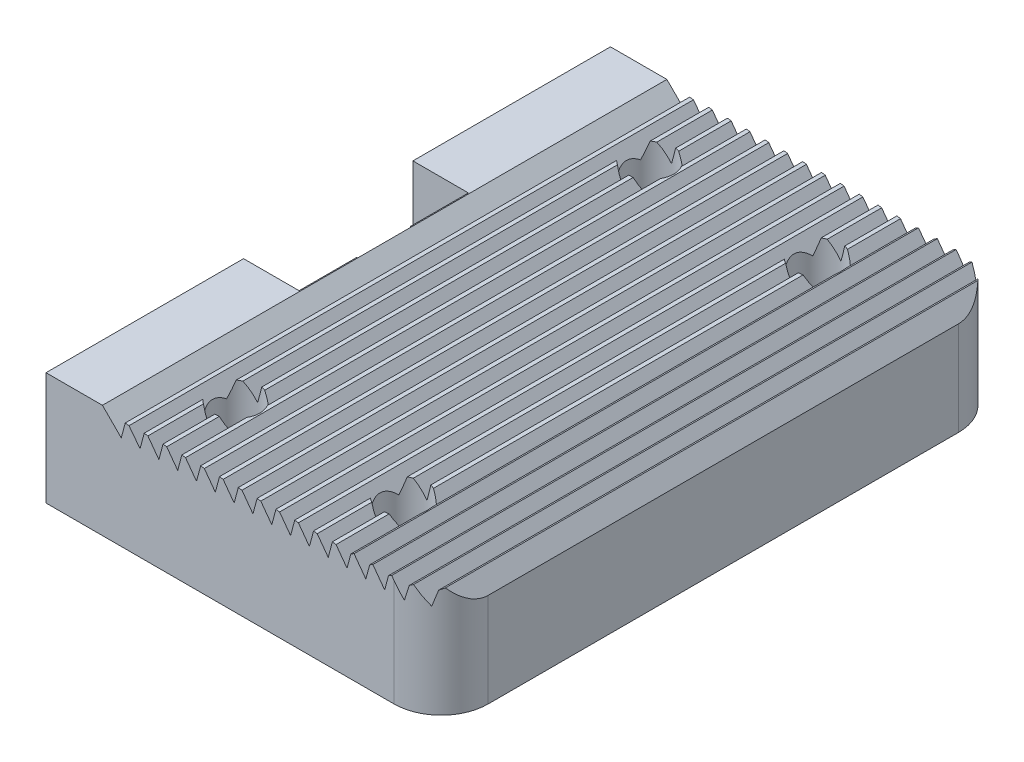
SolidWorks part; units mm, degrees
ref_plane "前视基准面" through (0, 0, 0) normal (0, 0, 1) x (1, 0, 0)
ref_plane "上视基准面" through (0, 0, 0) normal (0, 1, 0) x (1, 0, 0)
ref_plane "右视基准面" through (0, 0, 0) normal (1, 0, 0) x (0, 0, -1)
other "Configuration Table"
sketch "草图1" plane through (0, 0, 0) normal (0, 0, 1) x (1, 0, 0)
  line L0 (0, 0) -> (0, 10)
  line L2 (0, 10) -> (42, 10)
  line L3 (0, 0) -> (42, 0)
  line L4 (42, 10) -> (42, 0)
  line L5 (0, 10) -> (0, 12)
  line L6 (0, 12) -> (6, 12)
  line L7 (6, 12) -> (8, 10)
  line L8 (8, 10) -> (8.5176, 11.9319)
  line L9 (8.5176, 11.9319) -> (10, 10)
  line L10 (10, 10) -> (10.5359, 12)
  line L11 (10.5359, 12) -> (12, 10)
  line L12 (12, 10) -> (12.5359, 12)
  line L13 (12.5359, 12) -> (14, 10)
  line L14 (14, 10) -> (14.5359, 12)
  line L15 (14.5359, 12) -> (16, 10)
  line L16 (16, 10) -> (16.5359, 12)
  line L17 (16.5359, 12) -> (18, 10)
  line L18 (18, 10) -> (18.5359, 12)
  line L19 (18.5359, 12) -> (20, 10)
  line L20 (20, 10) -> (20.5359, 12)
  line L21 (20.5359, 12) -> (22, 10)
  line L22 (22, 10) -> (22.5359, 12)
  line L23 (22.5359, 12) -> (24, 10)
  line L24 (24, 10) -> (24.5359, 12)
  line L25 (24.5359, 12) -> (26, 10)
  line L26 (26, 10) -> (26.5359, 12)
  line L27 (26.5359, 12) -> (28, 10)
  line L28 (28, 10) -> (28.5359, 12)
  line L29 (28.5359, 12) -> (30, 10)
  line L30 (0, 12) -> (0, 10)
  line L31 (30, 10) -> (0, 10)
  line L32 (30, 10) -> (30.5359, 12)
  line L33 (30.5359, 12) -> (32, 10)
  line L34 (32, 10) -> (32.5359, 12)
  line L35 (32.5359, 12) -> (34, 10)
  line L36 (34, 10) -> (34.5359, 12)
  line L37 (34.5359, 12) -> (36, 10)
  line L38 (36, 10) -> (36.5359, 12)
  line L39 (36.5359, 12) -> (38, 10)
  line L40 (38, 10) -> (38.5359, 12)
  line L41 (38.5359, 12) -> (40, 10)
  line L42 (40, 10) -> (40.5359, 12)
  line L43 (40.5359, 12) -> (42, 10)
  point P6 (0, 0)
  dimension "D1" = 10
  dimension "D2" = 42
  dimension "D3" = 2
  dimension "D4" = 6
  dimension "D5" = 75
  dimension "D6" = 2
  dimension "D7" = 2
  dimension "D8" = 2
  dimension "D9" = 75
  dimension "D10" = 2
  dimension "D11" = 2
  dimension "D12" = 75
  dimension "D13" = 2
  dimension "D14" = 75
  dimension "D15" = 2
  dimension "D16" = 75
  dimension "D17" = 2
  dimension "D18" = 2
  dimension "D19" = 75
  dimension "D20" = 2
  dimension "D21" = 75
  dimension "D22" = 2
  dimension "D23" = 75
  dimension "D24" = 2
  dimension "D25" = 75
  dimension "D26" = 75
  dimension "D27" = 2
  dimension "D28" = 75
  dimension "D29" = 2
  dimension "D30" = 75
  dimension "D31" = 2
  dimension "D32" = 2
  dimension "D33" = 75
  dimension "D34" = 2
  dimension "D35" = 75
  dimension "D36" = 2
  dimension "D37" = 2
  dimension "D38" = 2
  dimension "D39" = 75
extrude "凸台-拉伸1" add sketch "草图1" along normal blind 60
fillet "圆角1" radius 5 2 edges at (42, 5, 0) (42, 5, 60)
sketch "草图2" plane through (0, 0, 0) normal (-1, 0, 0) x (0, 0, 1)
  line L0 (30, 12) -> (30, 0) construction
  line L1 (60, 12) -> (0, 12) construction
  line L2 (60, 0) -> (0, 0) construction
  line L3 (21, 12) -> (39, 12)
  line L4 (39, 12) -> (39, 0)
  line L5 (21, 0) -> (39, 0)
  line L6 (21, 12) -> (21, 0)
  circle A0 centre (30, 12) radius 2.9
  line M3 (0, 0) -> (60, 0)
  line M5 (60, 12) -> (0, 12)
  dimension "D1" = 5.8
  dimension "D2" = 9
extrude "切除-拉伸1" cut sketch "草图2" against normal blind 5.9 contours A0 L0 L5 L4 M5 | L0 A0 L6 M5 M3 | L3 L0 A0 | L0 A0 M5
chamfer "倒角1" distance 0.5 angle 45 17 edges at (40.5359, 12, 30) (38.5359, 12, 30) (36.5359, 12, 30) (34.5359, 12, 30) (32.5359, 12, 30) (30.5359, 12, 30) (28.5359, 12, 30) (26.5359, 12, 30) (24.5359, 12, 30) (22.5359, 12, 30) (20.5359, 12, 30) (18.5359, 12, 30) (16.5359, 12, 30) (14.5359, 12, 30) (12.5359, 12, 30) (10.5359, 12, 30) (8.5176, 11.9319, 30)
sketch "草图6" plane through (5.9, 0, 0) normal (-1, 0, 0) x (0, 0, 1)
  line L1 (39, 12) -> (21, 12) construction
  line L3 (27.05, 12) -> (32.95, 12)
  circle A1 centre (30, 12) radius 2.85
  dimension "D1" = 5.7
extrude "切除-拉伸2" cut sketch "草图6" against normal blind 0.1 contours A1
sketch "草图7" plane through (0, 0, 0) normal (0, -1, 0) x (1, 0, 0)
  line L0 (0, 60) -> (37, 60) construction
  line L1 (0, 60) -> (0, 39) construction
  line L2 (18.5, 60) -> (18.5, 0) construction
  line L3 (0, 0) -> (37, 0) construction
  line L4 (5.9, 30) -> (42, 30) construction
  line L5 (5.9, 21) -> (5.9, 39) construction
  line L6 (42, 55) -> (42, 5) construction
  line L7 (37, 60) -> (37, 0) construction
  line L8 (30, 52) -> (37, 52) construction
  circle A0 centre (12.2, 52) radius 2.5
  circle A1 centre (30, 52) radius 2.5
  circle A2 centre (30, 8) radius 2.5
  circle A3 centre (12.2, 8) radius 2.5
  dimension "D1" = 5
  dimension "D2" = 8
  dimension "D3" = 12.2
  dimension "D4" = 7
extrude "切除-拉伸3" cut sketch "草图7" against normal through all
